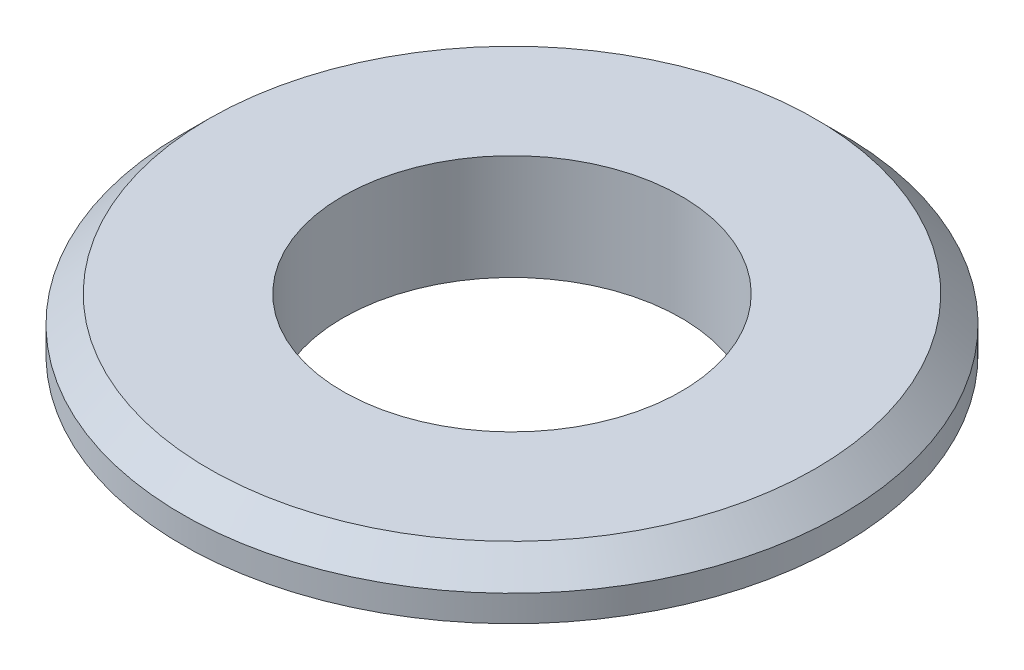
SolidWorks part; units mm, degrees
material "PTFE (general)"
ref_plane "Front Plane" through (0, 0, 0) normal (0, 0, 1) x (1, 0, 0)
ref_plane "Top Plane" through (0, 0, 0) normal (0, 1, 0) x (1, 0, 0)
ref_plane "Right Plane" through (0, 0, 0) normal (1, 0, 0) x (0, 0, -1)
sketch "Sketch1" plane through (0, 0, 0) normal (0, 0, 1) x (1, 0, 0)
  line L0 (-4.8895, 0) -> (-4.8895, -3.048)
  line L1 (-4.8895, -3.048) -> (-6.35, -3.048)
  line L2 (-6.35, -3.048) -> (-6.35, -1.524)
  line L3 (-6.35, -1.524) -> (-9.525, -1.524)
  line L4 (-9.525, -1.524) -> (-9.525, -0.762)
  line L5 (-9.525, -0.762) -> (-8.763, 0)
  line L6 (-8.763, 0) -> (-4.8895, 0)
  line L7 (0, 0) -> (0, -3.048) construction
  dimension "D" = 9.779
  dimension "A" = 19.05
  dimension "C" = 12.7
  dimension "LG" = 1.524
  dimension "D6" = 45
  dimension "B" = 1.524
  dimension "D7" = 0.762
revolve "Revolve1" add sketch "Sketch1" angle 360 about L7
equation "\"D7@Sketch1\" = \"B@Sketch1\"/2"
